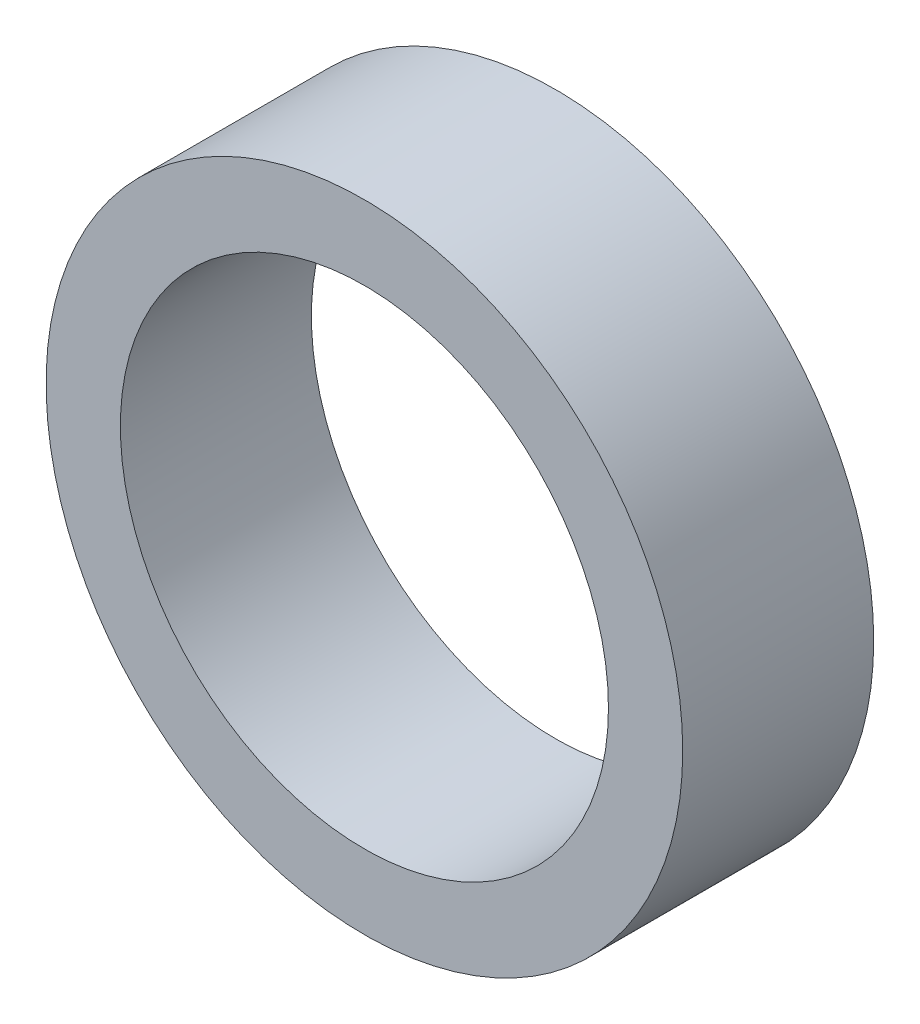
SolidWorks part; units mm, degrees
material "PUR"
ref_plane "前视基准面" through (0, 0, 0) normal (0, 0, 1) x (1, 0, 0)
ref_plane "上视基准面" through (0, 0, 0) normal (0, 1, 0) x (1, 0, 0)
ref_plane "右视基准面" through (0, 0, 0) normal (1, 0, 0) x (0, 0, -1)
sketch "草图1" plane through (0, 0, 0) normal (0, 0, 1) x (1, 0, 0)
  circle A0 centre (0, 0) radius 30
  circle A1 centre (0, 0) radius 23
  dimension "D1" = 46
  dimension "D2" = 60
extrude "凸台-拉伸1" add sketch "草图1" along normal blind 18
